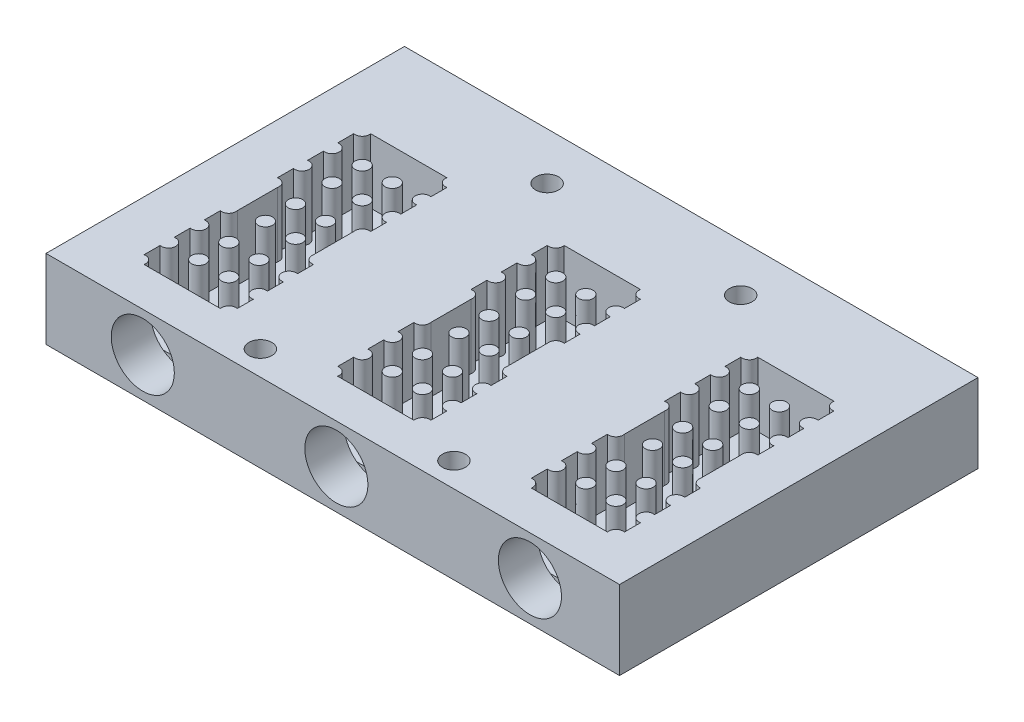
SolidWorks part; units mm, degrees
ref_plane "Ebene vorne" through (0, 0, 0) normal (0, 0, 1) x (1, 0, 0)
ref_plane "Ebene oben" through (0, 0, 0) normal (0, 1, 0) x (1, 0, 0)
ref_plane "Ebene rechts" through (0, 0, 0) normal (1, 0, 0) x (0, 0, -1)
sketch "Skizze1" plane through (0, 0, 0) normal (0, 1, 0) x (1, 0, 0)
  line L1 (0, 0) -> (80, 0)
  line L2 (0, 0) -> (0, 50)
  line L3 (0, 50) -> (80, 50)
  line L4 (80, 0) -> (80, 50)
  dimension "D1" = 80
  dimension "D2" = 50
extrude "Aufsatz-Linear austragen1" add sketch "Skizze1" along normal blind 11
sketch "Skizze2" plane through (0, 11, 0) normal (0, 1, 0) x (1, 0, 0)
  line L0 (0, 0) -> (80, 0) construction
  line L1 (0, 50) -> (0, 0) construction
  circle A0 centre (26.5, 3.4) radius 1.6
  circle A1 centre (53.5, 3.4) radius 1.6
  circle A2 centre (53.5, 43.4) radius 1.6
  circle A3 centre (26.5, 43.4) radius 1.6
  dimension "D1" = 3.2
  dimension "D3" = 26.5
  dimension "D6" = 40
  dimension "D7" = 27
  dimension "D2" = 3.4
  dimension "D4" = 2
  dimension "D5" = 2
extrude "Schnitt-Linear austragen1" cut sketch "Skizze2" against normal blind 11
sketch "Skizze3" plane through (0, 11, 0) normal (0, 1, 0) x (1, 0, 0)
  line L0 (0, 0) -> (80, 0) construction
  line L1 (7, 18.5) -> (20, 18.5)
  line L2 (7, 18.5) -> (7, 5.5)
  line L3 (7, 5.5) -> (20, 5.5)
  line L4 (20, 18.5) -> (20, 5.5)
  line L5 (0, 50) -> (0, 0) construction
  line L6 (34, 18.5) -> (47, 18.5)
  line L7 (34, 18.5) -> (34, 5.5)
  line L8 (34, 5.5) -> (47, 5.5)
  line L9 (47, 18.5) -> (47, 5.5)
  line L10 (61, 18.5) -> (74, 18.5)
  line L11 (61, 18.5) -> (61, 5.5)
  line L12 (61, 5.5) -> (74, 5.5)
  line L13 (74, 18.5) -> (74, 5.5)
  line L14 (34, 37.1) -> (47, 37.1)
  line L15 (34, 37.1) -> (34, 24.1)
  line L16 (34, 24.1) -> (47, 24.1)
  line L17 (47, 37.1) -> (47, 24.1)
  line L18 (61, 37.1) -> (74, 37.1)
  line L19 (61, 37.1) -> (61, 24.1)
  line L20 (61, 24.1) -> (74, 24.1)
  line L21 (74, 37.1) -> (74, 24.1)
  line L22 (7, 37.1) -> (20, 37.1)
  line L23 (7, 37.1) -> (7, 24.1)
  line L24 (7, 24.1) -> (20, 24.1)
  line L25 (20, 37.1) -> (20, 24.1)
  dimension "D1" = 13
  dimension "D2" = 13
  dimension "D3" = 5.5
  dimension "D4" = 7
  dimension "D5" = 3
  dimension "D6" = 2
extrude "Schnitt-Linear austragen2" cut sketch "Skizze3" against normal blind 9
hole_wizard "G1/8 Gewindebohrung1" positions "Skizze9" profile "Skizze7" tap size "G1/8" standard "GB"
sketch "Skizze9" plane through (0, 0, 0) normal (0, 0, 1) x (1, 0, 0)
  line L0 (0, 11) -> (0, 0) construction
  line L1 (0, 0) -> (80, 0) construction
  point P0 (13.5, 5.5)
  point P2 (40.5, 5.5)
  point P4 (67.5, 5.5)
  dimension "D1" = 13.5
  dimension "D2" = 27
  dimension "D3" = 27
  dimension "D4" = 5.5
sketch "Skizze7" plane through (13.5, 5.5, 0) normal (1, 0, 0) x (0, -1, 0)
  line L0 (0, 0) -> (0, 5.5)
  line L1 (0, 5.5) -> (4.4, 5.5)
  line L2 (4.4, 5.5) -> (4.4, 0)
  line L5 (4.4, 0) -> (0, 0)
  line L11 (0, -6.35) -> (0, 107.95) construction
  dimension "Bohrerdurchmesser" = 8.8
  dimension "Bohrungstiefe" = 5.5
cosmetic thread "Bohrungsgewinde1" parameters "D2"=9.728
cosmetic thread "Bohrungsgewinde2" parameters "D2"=9.728
cosmetic thread "Bohrungsgewinde3" parameters "D2"=9.728
sketch "Skizze10" plane through (0, 2, 0) normal (0, 1, 0) x (1, 0, 0)
  line L1 (7, 18.5) -> (7, 5.5) construction
  line L4 (7, 5.5) -> (20, 5.5) construction
  circle A1 centre (7.2, 5.7) radius 1.0001
  circle A4 centre (19.8, 5.7) radius 1.0001
  circle A5 centre (11.4, 9.9) radius 1.0001
  circle A6 centre (15.6, 9.9) radius 1.0001
  circle A7 centre (19.8, 9.9) radius 1.0001
  circle A8 centre (11.4, 14.1) radius 1.0001
  circle A9 centre (15.6, 14.1) radius 1.0001
  circle A10 centre (19.8, 14.1) radius 1.0001
  circle A13 centre (19.8, 18.3) radius 1.0001
  circle A14 centre (7.2, 9.9) radius 1.0001
  circle A15 centre (7.2, 14.1) radius 1.0001
  circle A16 centre (7.2, 18.3) radius 1.0001
  circle A17 centre (11.4, 5.7) radius 1.0001 [skipped]
  circle A18 centre (15.6, 5.7) radius 1.0001 [skipped]
  circle A19 centre (11.4, 18.3) radius 1.0001 [skipped]
  circle A20 centre (15.6, 18.3) radius 1.0001 [skipped]
  point P2 (7.3506, 5.8026)
  dimension "D1" = 2.0003
  dimension "D3" = 4
  dimension "D2" = 4
  dimension "D4" = 0.2
  dimension "D5" = 0.2
extrude "Aufsatz-Linear austragen2" add sketch "Skizze10" along normal blind 9
pattern_linear "Lineares Muster1" count 3 spacing 27 along (1, 0, 0) count 2 spacing 18.6 along (0, 0, -1) of "Aufsatz-Linear austragen2"
sketch "Skizze11" plane through (0, 11, 0) normal (0, 1, 0) x (1, 0, 0)
  line L0 (13.5, 5.5) -> (13.5, 53.3935) construction
  line L1 (8.1799, 5.5) -> (18.8201, 5.5) construction
  line L3 (8.1799, 18.5) -> (18.8201, 18.5)
  line L4 (8.1799, 18.5) -> (8.1799, 24.1)
  line L5 (8.1799, 24.1) -> (18.8201, 24.1)
  line L6 (18.8201, 18.5) -> (18.8201, 24.1)
extrude "Schnitt-Linear austragen3" cut sketch "Skizze11" against normal blind 9
pattern_linear "Lineares Muster2" count 3 spacing 27 along (1, 0, 0) of "Schnitt-Linear austragen3"
sketch "Skizze12" plane through (0, 2, 0) normal (0, 1, 0) x (1, 0, 0)
  line L0 (11.4, 14.1) -> (11.4, 28.5297) construction
  circle A0 centre (11.4, 19.2) radius 1
  circle A1 centre (15.6, 19.2) radius 1
  circle A2 centre (15.6, 23.4) radius 1
  circle A3 centre (11.4, 23.4) radius 1
  circle A5 centre (11.4, 14.1) radius 1.0001 construction
  point P2 (11.4, 17.4551)
  point P3 (11.4, 19.1635)
  dimension "D1" = 2
  dimension "D4" = 5.1
  dimension "D5" = 4.2
  dimension "D2" = 2
  dimension "D3" = 2
extrude "Aufsatz-Linear austragen3" add sketch "Skizze12" along normal blind 9
pattern_linear "Lineares Muster3" count 3 spacing 27 along (1, 0, 0) of "Aufsatz-Linear austragen3"
sketch "Skizze13" plane through (0, 11, 0) normal (0, 1, 0) x (1, 0, 0)
  circle A0 centre (26.5, 3.4) radius 2.851
  dimension "D1" = 5.7019
